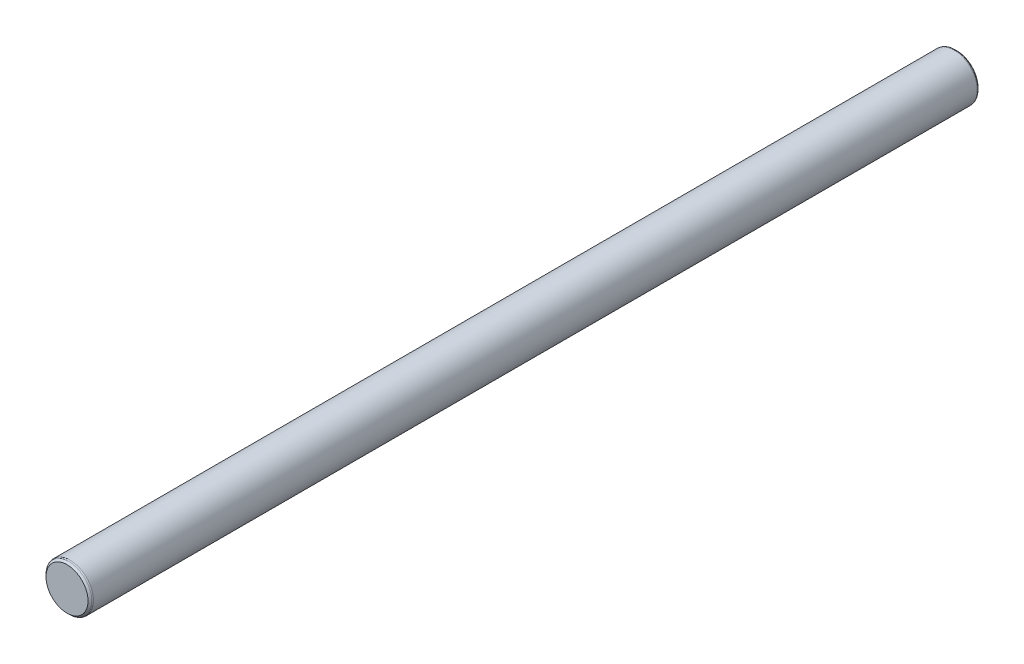
SolidWorks part; units mm, degrees
ref_plane "Front Plane" through (0, 0, 0) normal (0, 0, 1) x (1, 0, 0)
ref_plane "Top Plane" through (0, 0, 0) normal (0, 1, 0) x (1, 0, 0)
ref_plane "Right Plane" through (0, 0, 0) normal (1, 0, 0) x (0, 0, -1)
sketch "Sketch1" plane through (0, 0, 0) normal (0, 0, 1) x (1, 0, 0)
  line L0 (-3, 0) -> (3, 0) construction
  point P4 (0, 0)
  dimension "OD" = 6
sketch "Sketch2" plane through (0, 0, 0) normal (1, 0, 0) x (0, 0, -1)
  line L0 (457.2, 0) -> (-457.2, 0) construction
  line L1 (-457.2, 3) -> (-457.2, -3) construction
  line L2 (457.2, 3) -> (457.2, -3) construction
  point P0 (-450.3, 0)
  point P4 (0, 0)
  point P6 (450.3, 0)
  point P10 (457.2, 0)
  point P12 (-457.2, 0)
  dimension "Length" = 914.4
  dimension "D1" = 6.9
  dimension "D2" = 6.9
  dimension "D3" = 6
sketch "Sketch3" plane through (0, 0, 0) normal (0, 0, 1) x (1, 0, 0)
  circle A0 centre (0, 0) radius 3
extrude "Boss-Extrude1" add sketch "Sketch3" along normal mid plane 114.3
chamfer "Chamfer1" distance 0.3 angle 45 2 edges at (3, 0, 57.15) (3, 0, -57.15)
fillet "Fillet2" radius 0.225 2 edges at (3, 0, 56.85) (3, 0, -56.85)
equation "\"D1@Boss-Extrude1\"=\"Length@Sketch2\""
equation "\"D1@Chamfer1\"=\"OD@Sketch1\"*.05"
equation "\"D1@Fillet2\"=\"D1@Chamfer1\"*.75"
equation "\"D3@Sketch2\"=\"OD@Sketch1\""
equation "\"D1@Sketch2\"=\"OD@Sketch1\"*1.15"
equation "\"D2@Sketch2\"=\"D1@Sketch2\""
